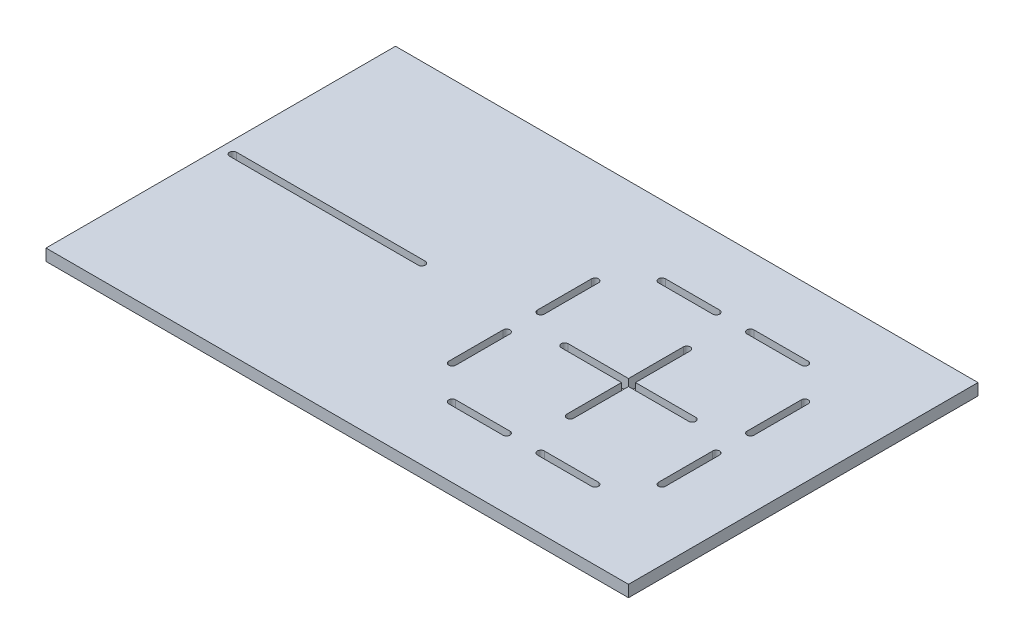
SolidWorks part; units mm, degrees
ref_plane "Front Plane" through (0, 0, 0) normal (0, 0, 1) x (1, 0, 0)
ref_plane "Top Plane" through (0, 0, 0) normal (0, 1, 0) x (1, 0, 0)
ref_plane "Right Plane" through (0, 0, 0) normal (1, 0, 0) x (0, 0, -1)
sketch "Sketch1" plane through (0, 0, 0) normal (0, 1, 0) x (1, 0, 0)
  line L1 (-54.3842, 257.5375) -> (445.6158, 257.5375)
  line L2 (-54.3842, 257.5375) -> (-54.3842, -42.4625)
  line L3 (-54.3842, -42.4625) -> (445.6158, -42.4625)
  line L4 (445.6158, 257.5375) -> (445.6158, -42.4625)
extrude "Boss-Extrude1" add sketch "Sketch1" along normal blind 10
sketch "Sketch2" plane through (0, 10, 0) normal (0, 1, 0) x (1, 0, 0)
  line L0 (-54.3842, 107.5375) -> (445.6158, 107.5375) construction
  line L1 (-54.3842, 257.5375) -> (-54.3842, -42.4625) construction
  line L2 (445.6158, -42.4625) -> (445.6158, 257.5375) construction
  line L3 (295.6158, 257.5375) -> (295.6158, -42.4625) construction
  line L4 (445.6158, 257.5375) -> (-54.3842, 257.5375) construction
  line L5 (-54.3842, -42.4625) -> (445.6158, -42.4625) construction
  line L6 (205.6158, 168.8297) -> (205.6158, 122.2426) construction
  line L7 (208.6158, 168.8297) -> (208.6158, 122.2426)
  line L8 (202.6158, 168.8297) -> (202.6158, 122.2426)
  line L9 (205.6158, 46.2453) -> (205.6158, 92.8323) construction
  line L10 (208.6158, 46.2453) -> (208.6158, 92.8323)
  line L11 (202.6158, 46.2453) -> (202.6158, 92.8323)
  line L12 (356.9081, 197.5375) -> (310.321, 197.5375) construction
  line L13 (356.9081, 194.5375) -> (310.321, 194.5375)
  line L14 (356.9081, 200.5375) -> (310.321, 200.5375)
  line L15 (234.3236, 197.5375) -> (280.9107, 197.5375) construction
  line L16 (234.3236, 194.5375) -> (280.9107, 194.5375)
  line L17 (234.3236, 200.5375) -> (280.9107, 200.5375)
  line L18 (385.6158, 46.2453) -> (385.6158, 92.8323) construction
  line L19 (382.6158, 46.2453) -> (382.6158, 92.8323)
  line L20 (388.6158, 46.2453) -> (388.6158, 92.8323)
  line L21 (385.6158, 168.8297) -> (385.6158, 122.2426) construction
  line L22 (382.6158, 168.8297) -> (382.6158, 122.2426)
  line L23 (388.6158, 168.8297) -> (388.6158, 122.2426)
  line L24 (234.3236, 17.5375) -> (280.9107, 17.5375) construction
  line L25 (234.3236, 20.5375) -> (280.9107, 20.5375)
  line L26 (234.3236, 14.5375) -> (280.9107, 14.5375)
  line L27 (356.9081, 17.5375) -> (310.321, 17.5375) construction
  line L28 (356.9081, 20.5375) -> (310.321, 20.5375)
  line L29 (356.9081, 14.5375) -> (310.321, 14.5375)
  arc A0 (208.6158, 168.8297) -> (202.6158, 168.8297) centre (205.6158, 168.8297) ccw
  arc A1 (202.6158, 122.2426) -> (208.6158, 122.2426) centre (205.6158, 122.2426) ccw
  arc A2 (208.6158, 46.2453) -> (202.6158, 46.2453) centre (205.6158, 46.2453) cw
  arc A3 (202.6158, 92.8323) -> (208.6158, 92.8323) centre (205.6158, 92.8323) cw
  arc A4 (356.9081, 194.5375) -> (356.9081, 200.5375) centre (356.9081, 197.5375) ccw
  arc A5 (310.321, 200.5375) -> (310.321, 194.5375) centre (310.321, 197.5375) ccw
  arc A6 (234.3236, 194.5375) -> (234.3236, 200.5375) centre (234.3236, 197.5375) cw
  arc A7 (280.9107, 200.5375) -> (280.9107, 194.5375) centre (280.9107, 197.5375) cw
  arc A8 (382.6158, 46.2453) -> (388.6158, 46.2453) centre (385.6158, 46.2453) ccw
  arc A9 (388.6158, 92.8323) -> (382.6158, 92.8323) centre (385.6158, 92.8323) ccw
  arc A10 (382.6158, 168.8297) -> (388.6158, 168.8297) centre (385.6158, 168.8297) cw
  arc A11 (388.6158, 122.2426) -> (382.6158, 122.2426) centre (385.6158, 122.2426) cw
  arc A12 (234.3236, 20.5375) -> (234.3236, 14.5375) centre (234.3236, 17.5375) ccw
  arc A13 (280.9107, 14.5375) -> (280.9107, 20.5375) centre (280.9107, 17.5375) ccw
  arc A14 (356.9081, 20.5375) -> (356.9081, 14.5375) centre (356.9081, 17.5375) cw
  arc A15 (310.321, 14.5375) -> (310.321, 20.5375) centre (310.321, 17.5375) cw
  point P14 (205.6158, 145.5362)
  point P22 (205.6158, 69.5388)
  point P31 (333.6145, 197.5375)
  point P38 (257.6172, 197.5375)
  point P45 (385.6158, 69.5388)
  point P52 (385.6158, 145.5362)
  point P59 (257.6172, 17.5375)
  point P66 (333.6145, 17.5375)
  point P71 (295.6158, 107.5375)
  dimension "D2" = 90
  dimension "D1" = 150
  dimension "D3" = 4
extrude "Cut-Extrude1" cut sketch "Sketch2" against normal blind 10
sketch "Sketch6" plane through (0, 10, 0) normal (0, 1, 0) x (1, 0, 0)
  line L0 (445.6158, 107.5375) -> (-54.3842, 107.5375) construction
  line L1 (445.6158, -42.4625) -> (445.6158, 257.5375) construction
  line L2 (-54.3842, 257.5375) -> (-54.3842, -42.4625) construction
  line L3 (295.6158, -42.4625) -> (295.6158, 257.5375) construction
  line L4 (-54.3842, -42.4625) -> (445.6158, -42.4625) construction
  line L5 (445.6158, 257.5375) -> (-54.3842, 257.5375) construction
  line L6 (-43.9007, 107.5375) -> (118.1126, 107.5375) construction
  line L7 (-43.9007, 110.5375) -> (118.1126, 110.5375)
  line L8 (-43.9007, 104.5375) -> (118.1126, 104.5375)
  arc A0 (-43.9007, 110.5375) -> (-43.9007, 104.5375) centre (-43.9007, 107.5375) ccw
  arc A1 (118.1126, 104.5375) -> (118.1126, 110.5375) centre (118.1126, 107.5375) ccw
  point P14 (37.1059, 107.5375)
  dimension "D1" = 150
extrude "Cut-Extrude2" cut sketch "Sketch6" against normal through all
sketch "Sketch7" plane through (0, 10, 0) normal (0, 1, 0) x (1, 0, 0)
  line L0 (-54.3842, 107.5375) -> (445.6158, 107.5375) construction
  line L1 (-54.3842, 257.5375) -> (-54.3842, -42.4625) construction
  line L2 (445.6158, -42.4625) -> (445.6158, 257.5375) construction
  line L3 (295.6158, 257.5375) -> (295.6158, -42.4625) construction
  line L4 (292.6158, 110.5375) -> (292.6158, 157.5375)
  line L5 (-54.3842, -42.4625) -> (445.6158, -42.4625) construction
  line L6 (445.6158, 257.5375) -> (-54.3842, 257.5375) construction
  line L7 (295.6158, 57.5375) -> (295.6158, 157.5375) construction
  line L8 (292.6158, 57.5375) -> (292.6158, 104.5375)
  line L9 (298.6158, 57.5375) -> (298.6158, 104.5375)
  line L10 (240.8754, 107.5375) -> (350.3563, 107.5375) construction
  line L11 (240.8754, 110.5375) -> (292.6158, 110.5375)
  line L12 (240.8754, 104.5375) -> (292.6158, 104.5375)
  line L13 (298.6158, 110.5375) -> (350.3563, 110.5375)
  line L14 (298.6158, 110.5375) -> (298.6158, 157.5375)
  line L15 (298.6158, 104.5375) -> (350.3563, 104.5375)
  arc A0 (292.6158, 57.5375) -> (298.6158, 57.5375) centre (295.6158, 57.5375) ccw
  arc A1 (298.6158, 157.5375) -> (292.6158, 157.5375) centre (295.6158, 157.5375) ccw
  arc A2 (240.8754, 110.5375) -> (240.8754, 104.5375) centre (240.8754, 107.5375) ccw
  arc A3 (350.3563, 104.5375) -> (350.3563, 110.5375) centre (350.3563, 107.5375) ccw
  point P8 (295.6158, 107.5375)
  point P21 (295.6158, 107.5375)
  dimension "D1" = 150
extrude "Cut-Extrude3" cut sketch "Sketch7" against normal through all
